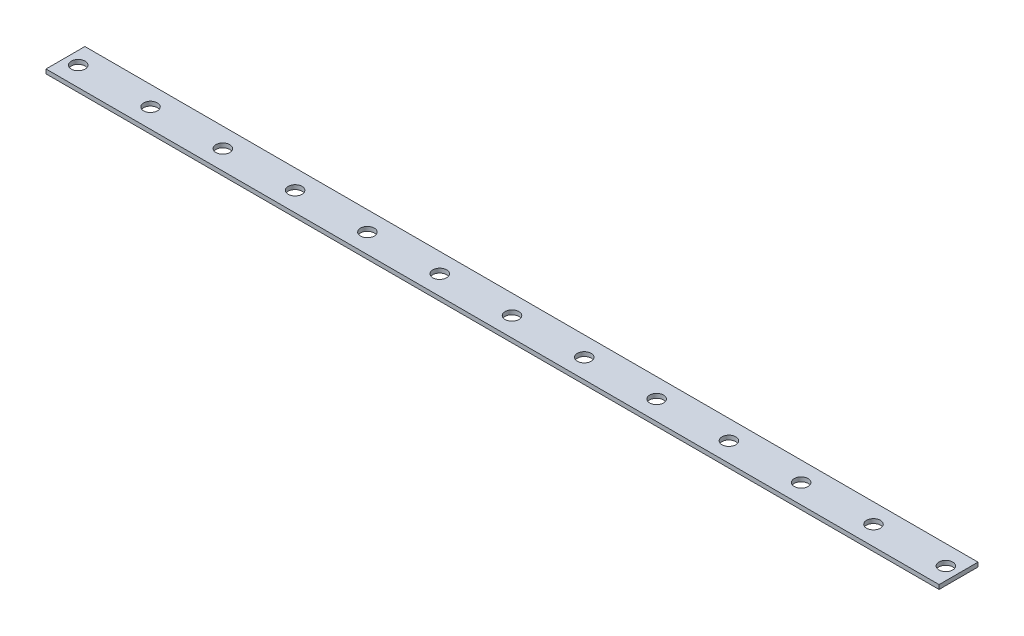
SolidWorks part; units mm, degrees
ref_plane "Front Plane" through (0, 0, 0) normal (0, 0, 1) x (1, 0, 0)
ref_plane "Top Plane" through (0, 0, 0) normal (0, 1, 0) x (1, 0, 0)
ref_plane "Right Plane" through (0, 0, 0) normal (1, 0, 0) x (0, 0, -1)
sketch "Sketch1" plane through (0, 0, 0) normal (0, 1, 0) x (1, 0, 0)
  line L0 (-459.5448, 0) -> (429.6654, 0) construction
  line L1 (-210, 9.15) -> (-210, -9.15)
  line L2 (-210, 9.15) -> (210, 9.15)
  line L3 (-210, -9.15) -> (210, -9.15)
  line L4 (0, 11.4722) -> (0, -16.6655) construction
  line L5 (210, 9.15) -> (210, -9.15)
  circle A0 centre (-204, 0) radius 3.25
  circle A1 centre (-170, 0) radius 3.25
  circle A2 centre (-136, 0) radius 3.25
  circle A3 centre (-102, 0) radius 3.25
  circle A4 centre (-68, 0) radius 3.25
  circle A5 centre (-34, 0) radius 3.25
  circle A6 centre (0, 0) radius 3.25
  circle A7 centre (34, 0) radius 3.25
  circle A30 centre (68, 0) radius 3.25
  circle A31 centre (102, 0) radius 3.25
  circle A32 centre (136, 0) radius 3.25
  circle A33 centre (170, 0) radius 3.25
  circle A34 centre (204, 0) radius 3.25
  point P6 (-210, 0)
  point P11 (0, -9.15)
  point P12 (0, 9.15)
  dimension "D2" = 6.5
  dimension "D1" = 210
  dimension "D3" = 18.3
  dimension "D4" = 6
  dimension "D6" = 34
  dimension "D7" = 6
  dimension "D5" = 13
extrude "Boss-Extrude1" add sketch "Sketch1" along normal mid plane 2
